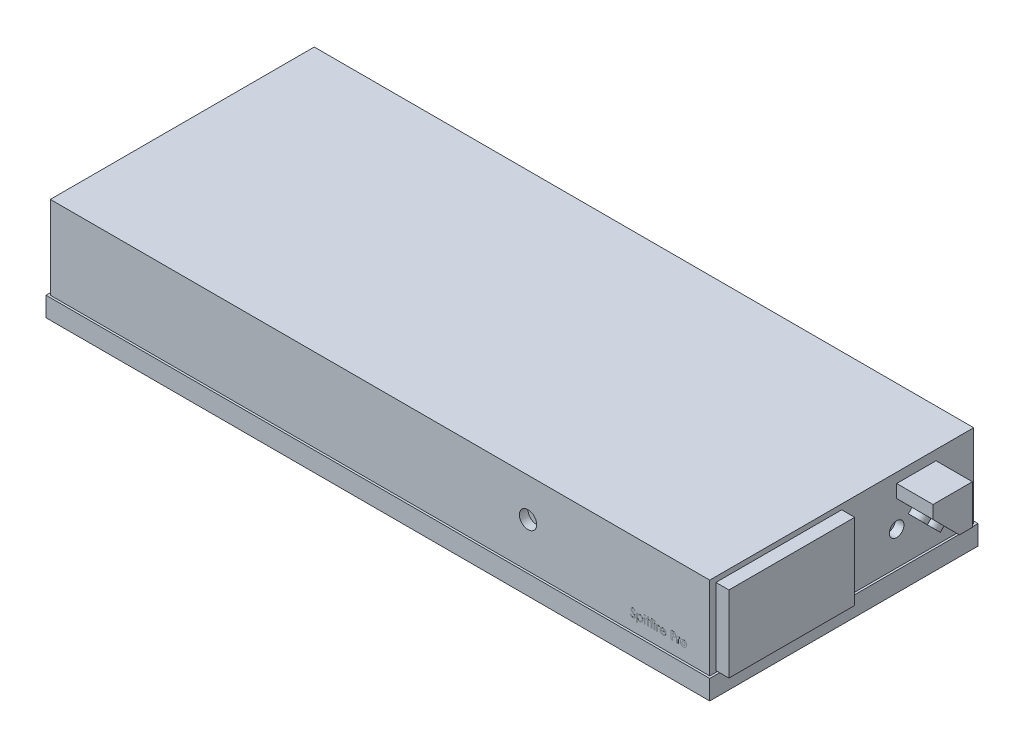
SolidWorks part; units mm, degrees
ref_plane "정면" through (0, 0, 0) normal (0, 0, 1) x (1, 0, 0)
ref_plane "윗면" through (0, 0, 0) normal (0, 1, 0) x (1, 0, 0)
ref_plane "우측면" through (0, 0, 0) normal (1, 0, 0) x (0, 0, -1)
sketch "스케치1" plane through (0, 0, 0) normal (0, 1, 0) x (1, 0, 0)
  line L1 (762, 305) -> (-762, 305)
  line L2 (762, 305) -> (762, -305)
  line L3 (762, -305) -> (-762, -305)
  line L4 (-762, 305) -> (-762, -305)
  line L5 (762, 305) -> (-762, -305) construction
  line L6 (762, -305) -> (-762, 305) construction
  point P0 (0, 0)
  dimension "D1" = 610
  dimension "D2" = 1524
extrude "보스-돌출1" add sketch "스케치1" along normal blind 237
sketch "스케치2" plane through (762, 0, 0) normal (1, 0, 0) x (0, 0, -1)
  line L2 (127, 184.3086) -> (127, 214.3086)
  line L3 (127, 214.3086) -> (218, 214.3086)
  line L4 (218, 214.3086) -> (218, 123)
  line L5 (218, 123) -> (188, 123)
  line L6 (127, 184.3086) -> (188, 123)
extrude "보스-돌출2" add sketch "스케치2" along normal blind 84 contours L3 L4 L5 L6 L2
sketch "스케치6" plane through (762, 0, 0) normal (1, 0, 0) x (0, 0, -1)
  line L0 (335.5, 0) -> (-335.5, 0) construction
  line L1 (305, 237) -> (305, 0) construction
  circle A0 centre (127, 123) radius 16.8806
  dimension "D1" = 123
  dimension "D2" = 178
extrude "컷-돌출1" cut sketch "스케치6" against normal blind 20
sketch "스케치7" plane through (0, 0, 305) normal (0, 0, 1) x (1, 0, 0)
  line L0 (762, 237) -> (762, 0) construction
  line L1 (-762, 0) -> (762, 0) construction
  circle A0 centre (342, 148) radius 20
  dimension "D1" = 420
  dimension "D2" = 148
extrude "컷-돌출2" cut sketch "스케치7" against normal blind 20
sketch "스케치8" plane through (762, 0, 0) normal (1, 0, 0) x (0, 0, -1)
  line L1 (-290.6796, 225.1548) -> (0, 225.1548)
  line L2 (-290.6796, 225.1548) -> (-290.6796, 48.7224)
  line L3 (-290.6796, 48.7224) -> (0, 48.7224)
  line L4 (0, 225.1548) -> (0, 48.7224)
extrude "보스-돌출3" add sketch "스케치8" along normal blind 30
sketch "스케치9" plane through (0, 155.1885, -155.9735) normal (0, -0.7053, 0.7089) x (1, 0, 0)
  line L3 (846, 41.0785) -> (846, -45.407) construction
  line L4 (846, 41.0785) -> (762, 41.0785) construction
  line L5 (846, -45.407) -> (762, -45.407) construction
  circle A0 centre (804, 19.0785) radius 18
  circle A1 centre (804, -23.407) radius 18
  dimension "D1" = 42
  dimension "D2" = 42
  dimension "D3" = 22
  dimension "D4" = 22
extrude "보스-돌출4" add sketch "스케치9" along normal blind 12
sketch "스케치10" plane through (762, 0, 0) normal (1, 0, 0) x (0, 0, -1)
  line L0 (335.5, 0) -> (-335.5, 0) construction
  line L1 (-305, 45.1939) -> (305, 45.1939)
  line L2 (-305, 45.1939) -> (-305, 0)
  line L3 (-305, 0) -> (305, 0)
  line L4 (305, 45.1939) -> (305, 0)
  line L5 (305, 237) -> (305, 0) construction
  line L6 (-305, 237) -> (-305, 0) construction
extrude "보스-돌출6" add sketch "스케치10" along normal blind 5
sketch "스케치11" plane through (-762, 0, 0) normal (-1, 0, 0) x (0, 0, 1)
  line L1 (9, 211) -> (169, 211)
  line L2 (9, 211) -> (9, 111)
  line L3 (9, 111) -> (169, 111)
  line L4 (169, 211) -> (169, 111)
  line L6 (-305, 0) -> (305, 0) construction
  line L7 (305, 237) -> (305, 0) construction
  point P6 (89, 161)
  dimension "D1" = 161
  dimension "D2" = 216
extrude "보스-돌출7" add sketch "스케치11" along normal blind 20
sketch "스케치12" plane through (-782, 0, 0) normal (-1, 0, 0) x (0, 0, 1)
  line L2 (305, 237) -> (305, 0) construction
  line L3 (-305, 0) -> (305, 0) construction
  circle A0 centre (89, 161) radius 16
  dimension "D1" = 216
  dimension "D2" = 161
extrude "컷-돌출3" cut sketch "스케치12" against normal blind 20
sketch "스케치13" plane through (-762, 0, 0) normal (-1, 0, 0) x (0, 0, 1)
  line L1 (-305, 45.1939) -> (305, 45.1939)
  line L2 (-305, 45.1939) -> (-305, 0)
  line L3 (-305, 0) -> (305, 0)
  line L4 (305, 45.1939) -> (305, 0)
extrude "보스-돌출8" add sketch "스케치13" along normal blind 5
sketch "스케치14" plane through (0, 0, 305) normal (0, 0, 1) x (1, 0, 0)
  line L1 (-767, 45.1939) -> (767, 45.1939)
  line L2 (-767, 45.1939) -> (-767, 0)
  line L3 (-767, 0) -> (767, 0)
  line L4 (767, 45.1939) -> (767, 0)
extrude "보스-돌출9" add sketch "스케치14" along normal blind 5
sketch "스케치15" plane through (0, 0, -305) normal (0, 0, -1) x (-1, 0, 0)
  line L0 (338.25, 0) -> (-338.25, 0) construction
  line L1 (767, 45.1939) -> (-767, 45.1939)
  line L2 (767, 45.1939) -> (767, 0)
  line L3 (767, 0) -> (-767, 0)
  line L4 (-767, 45.1939) -> (-767, 0)
  line L5 (-767, 0) -> (-767, 45.1939) construction
extrude "보스-돌출10" add sketch "스케치15" along normal blind 5
sketch "스케치17" plane through (0, 0, 305) normal (0, 0, 1) x (1, 0, 0)
  text T0 "Spitfire <b>Pro</b>" font "Century Gothic" height in points 72
extrude "보스-돌출11" add sketch "스케치17" along normal blind 0.1
